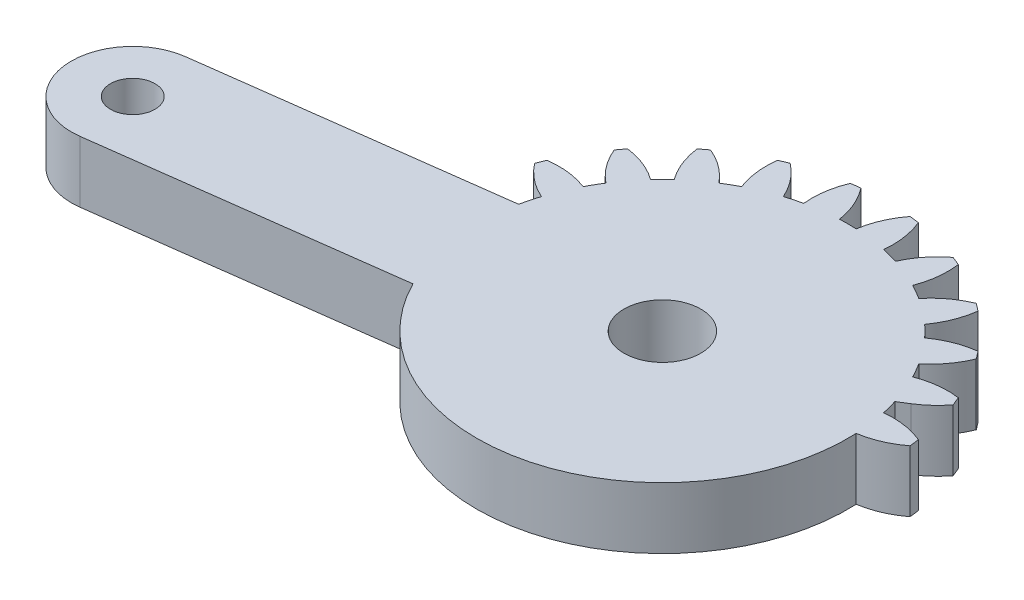
SolidWorks part; units mm, degrees
ref_plane "Front Plane" through (0, 0, 0) normal (0, 0, 1) x (1, 0, 0)
ref_plane "Top Plane" through (0, 0, 0) normal (0, 1, 0) x (1, 0, 0)
ref_plane "Right Plane" through (0, 0, 0) normal (1, 0, 0) x (0, 0, -1)
sketch "Sketch1" plane through (0, 0, 0) normal (0, 1, 0) x (1, 0, 0)
  line L0 (20.6437, 4) -> (2.0816, 4)
  line L1 (2.0816, -4) -> (20.6437, -4)
  arc A0 (2.0816, 4) -> (3.5217, 5.3071) centre (-0.7683, 8.5867) ccw
  arc A1 (3.5217, 5.3071) -> (3.2829, 5.8838) centre (-10.1063, 0) ccw
  arc A2 (3.2829, 5.8838) -> (0.6271, 5.5703) centre (2.5684, 0.5313) ccw
  arc A3 (0.6271, 5.5703) -> (0.0844, 6.5103) centre (-10.1063, 0) ccw
  arc A4 (0.0844, 6.5103) -> (1.6838, 8.6535) centre (-3.3089, 10.711) ccw
  arc A5 (1.6838, 8.6535) -> (1.3038, 9.1487) centre (-10.1063, 0) ccw
  arc A6 (1.3038, 9.1487) -> (-1.1803, 8.1585) centre (1.999, 3.7936) ccw
  arc A7 (-1.1803, 8.1585) -> (-1.9479, 8.926) centre (-10.1063, 0) ccw
  arc A8 (-1.9479, 8.926) -> (-0.9576, 11.4102) centre (-6.3127, 12.1053) ccw
  arc A9 (-0.9576, 11.4102) -> (-1.4528, 11.7901) centre (-10.1063, 0) ccw
  arc A10 (-1.4528, 11.7901) -> (-3.596, 10.1907) centre (0.6046, 6.7975) ccw
  arc A11 (-3.596, 10.1907) -> (-4.5361, 10.7334) centre (-10.1063, 0) ccw
  arc A12 (-4.5361, 10.7334) -> (-4.2225, 13.3892) centre (-9.5751, 12.6747) ccw
  arc A13 (-4.2225, 13.3892) -> (-4.7992, 13.6281) centre (-10.1063, 0) ccw
  arc A14 (-4.7992, 13.6281) -> (-6.4554, 11.5285) centre (-1.5196, 9.3381) ccw
  arc A15 (-6.4554, 11.5285) -> (-7.5039, 11.8094) centre (-10.1063, 0) ccw
  arc A16 (-7.5039, 11.8094) -> (-7.8884, 14.4558) centre (-12.8736, 12.3803) ccw
  arc A17 (-7.8884, 14.4558) -> (-8.5072, 14.5373) centre (-10.1063, 0) ccw
  arc A18 (-8.5072, 14.5373) -> (-9.5636, 12.0806) centre (-4.2291, 11.2423) ccw
  arc A19 (-9.5636, 12.0806) -> (-10.6491, 12.0806) centre (-10.1063, 0) ccw
  arc A20 (-10.6491, 12.0806) -> (-11.7054, 14.5373) centre (-15.9836, 11.2423) ccw
  arc A21 (-11.7054, 14.5373) -> (-12.3243, 14.4558) centre (-10.1063, 0) ccw
  arc A22 (-12.3243, 14.4558) -> (-12.7088, 11.8094) centre (-7.3391, 12.3803) ccw
  arc A23 (-12.7088, 11.8094) -> (-13.7573, 11.5285) centre (-10.1063, 0) ccw
  arc A24 (-13.7573, 11.5285) -> (-15.4135, 13.6281) centre (-18.6931, 9.3381) ccw
  arc A25 (-15.4135, 13.6281) -> (-15.9901, 13.3892) centre (-10.1063, 0) ccw
  arc A26 (-15.9901, 13.3892) -> (-15.6766, 10.7334) centre (-10.6376, 12.6747) ccw
  arc A27 (-15.6766, 10.7334) -> (-16.6166, 10.1907) centre (-10.1063, 0) ccw
  arc A28 (-16.6166, 10.1907) -> (-18.7599, 11.7901) centre (-20.8173, 6.7975) ccw
  arc A29 (-18.7599, 11.7901) -> (-19.255, 11.4102) centre (-10.1063, 0) ccw
  arc A30 (-19.255, 11.4102) -> (-18.2648, 8.926) centre (-13.9, 12.1053) ccw
  arc A31 (-18.2648, 8.926) -> (-19.0324, 8.1585) centre (-10.1063, 0) ccw
  arc A32 (-19.0324, 8.1585) -> (-21.5165, 9.1487) centre (-22.2117, 3.7936) ccw
  arc A33 (-21.5165, 9.1487) -> (-21.8965, 8.6535) centre (-10.1063, 0) ccw
  arc A34 (-21.8965, 8.6535) -> (-20.2971, 6.5103) centre (-16.9038, 10.711) ccw
  arc A35 (-20.2971, 6.5103) -> (-20.8398, 5.5703) centre (-10.1063, 0) ccw
  arc A36 (-20.8398, 5.5703) -> (-23.4956, 5.8838) centre (-22.7811, 0.5313) ccw
  arc A37 (-23.4956, 5.8838) -> (-23.7344, 5.3071) centre (-10.1063, 0) ccw
  arc A38 (-23.7344, 5.3071) -> (-21.6348, 3.6509) centre (-19.4444, 8.5867) ccw
  arc A39 (-21.6348, 3.6509) -> (-21.9157, 2.6025) centre (-10.1063, 0) ccw
  arc A40 (-21.9157, 2.6025) -> (-24.5622, 2.2179) centre (-22.4867, -2.7673) ccw
  arc A41 (-24.5622, 2.2179) -> (-24.6437, 1.5991) centre (-10.1063, 0) ccw
  arc A42 (-24.6437, 1.5991) -> (-22.1869, 0.5427) centre (-21.3486, 5.8773) ccw
  arc A43 (-22.1869, 0.5427) -> (-22.1869, -0.5427) centre (-10.1063, 0) ccw
  arc A44 (-22.1869, -0.5427) -> (-24.6437, -1.5991) centre (-21.3486, -5.8773) ccw
  arc A45 (-24.6437, -1.5991) -> (-24.5622, -2.2179) centre (-10.1063, 0) ccw
  arc A46 (-24.5622, -2.2179) -> (-21.9157, -2.6025) centre (-22.4867, 2.7673) ccw
  arc A47 (-21.9157, -2.6025) -> (-21.6348, -3.6509) centre (-10.1063, 0) ccw
  arc A48 (-21.6348, -3.6509) -> (-23.7344, -5.3071) centre (-19.4444, -8.5867) ccw
  arc A49 (-23.7344, -5.3071) -> (-23.4956, -5.8838) centre (-10.1063, 0) ccw
  arc A50 (-23.4956, -5.8838) -> (-20.8398, -5.5703) centre (-22.7811, -0.5313) ccw
  arc A51 (-20.8398, -5.5703) -> (-20.2971, -6.5103) centre (-10.1063, 0) ccw
  arc A52 (-20.2971, -6.5103) -> (-21.8965, -8.6535) centre (-16.9038, -10.711) ccw
  arc A53 (-21.8965, -8.6535) -> (-21.5165, -9.1487) centre (-10.1063, 0) ccw
  arc A54 (-21.5165, -9.1487) -> (-19.0324, -8.1585) centre (-22.2117, -3.7936) ccw
  arc A55 (-19.0324, -8.1585) -> (-18.2648, -8.926) centre (-10.1063, 0) ccw
  arc A56 (-18.2648, -8.926) -> (-19.255, -11.4102) centre (-13.9, -12.1053) ccw
  arc A57 (-19.255, -11.4102) -> (-18.7599, -11.7901) centre (-10.1063, 0) ccw
  arc A58 (-18.7599, -11.7901) -> (-16.6166, -10.1907) centre (-20.8173, -6.7975) ccw
  arc A59 (-16.6166, -10.1907) -> (-15.6766, -10.7334) centre (-10.1063, 0) ccw
  arc A60 (-15.6766, -10.7334) -> (-15.9901, -13.3892) centre (-10.6376, -12.6747) ccw
  arc A61 (-15.9901, -13.3892) -> (-15.4135, -13.6281) centre (-10.1063, 0) ccw
  arc A62 (-15.4135, -13.6281) -> (-13.7573, -11.5285) centre (-18.6931, -9.3381) ccw
  arc A63 (-13.7573, -11.5285) -> (-12.7088, -11.8094) centre (-10.1063, 0) ccw
  arc A64 (-12.7088, -11.8094) -> (-12.3243, -14.4558) centre (-7.3391, -12.3803) ccw
  arc A65 (-12.3243, -14.4558) -> (-11.7054, -14.5373) centre (-10.1063, 0) ccw
  arc A66 (-11.7054, -14.5373) -> (-10.6491, -12.0806) centre (-15.9836, -11.2423) ccw
  arc A67 (-10.6491, -12.0806) -> (-9.5636, -12.0806) centre (-10.1063, 0) ccw
  arc A68 (-9.5636, -12.0806) -> (-8.5072, -14.5373) centre (-4.2291, -11.2423) ccw
  arc A69 (-8.5072, -14.5373) -> (-7.8884, -14.4558) centre (-10.1063, 0) ccw
  arc A70 (-7.8884, -14.4558) -> (-7.5039, -11.8094) centre (-12.8736, -12.3803) ccw
  arc A71 (-7.5039, -11.8094) -> (-6.4554, -11.5285) centre (-10.1063, 0) ccw
  arc A72 (-6.4554, -11.5285) -> (-4.7992, -13.6281) centre (-1.5196, -9.3381) ccw
  arc A73 (-4.7992, -13.6281) -> (-4.2225, -13.3892) centre (-10.1063, 0) ccw
  arc A74 (-4.2225, -13.3892) -> (-4.5361, -10.7334) centre (-9.5751, -12.6747) ccw
  arc A75 (-4.5361, -10.7334) -> (-3.596, -10.1907) centre (-10.1063, 0) ccw
  arc A76 (-3.596, -10.1907) -> (-1.4528, -11.7901) centre (0.6046, -6.7975) ccw
  arc A77 (-1.4528, -11.7901) -> (-0.9576, -11.4102) centre (-10.1063, 0) ccw
  arc A78 (-0.9576, -11.4102) -> (-1.9479, -8.926) centre (-6.3127, -12.1053) ccw
  arc A79 (-1.9479, -8.926) -> (-1.1803, -8.1585) centre (-10.1063, 0) ccw
  arc A80 (-1.1803, -8.1585) -> (1.3038, -9.1487) centre (1.999, -3.7936) ccw
  arc A81 (1.3038, -9.1487) -> (1.6838, -8.6535) centre (-10.1063, 0) ccw
  arc A82 (1.6838, -8.6535) -> (0.0844, -6.5103) centre (-3.3089, -10.711) ccw
  arc A83 (0.0844, -6.5103) -> (0.6271, -5.5703) centre (-10.1063, 0) ccw
  arc A84 (0.6271, -5.5703) -> (3.2829, -5.8838) centre (2.5684, -0.5313) ccw
  arc A85 (3.2829, -5.8838) -> (3.5217, -5.3071) centre (-10.1063, 0) ccw
  arc A86 (3.5217, -5.3071) -> (2.0816, -4) centre (-0.7683, -8.5867) ccw
  arc A87 (20.6437, -4) -> (20.6437, 4) centre (20.6437, 0) ccw
  circle A88 centre (-10.1063, 0) radius 1.5
  circle A89 centre (20.6437, 0) radius 1.5
  dimension "D1" = 3
  dimension "D2" = 3
extrude "Boss-Extrude1" add sketch "Sketch1" along normal blind 4
sketch "Sketch3" plane through (0, 4, 0) normal (0, 1, 0) x (1, 0, 0)
  line L0 (-10.1063, 0) -> (-40.8563, 0) construction
  line L1 (-10.1063, 0) -> (-40.5933, -4.0137)
  line L2 (-10.6284, 3.9658) -> (-41.1154, -0.0479)
  line L3 (-9.5842, -3.9658) -> (-40.0712, -7.9795)
  line L4 (-10.1063, 0) -> (-4.5096, 13.5117) construction
  line L5 (-10.1063, 0) -> (-8.1974, 14.4999) construction
  circle A0 centre (-10.1063, 0) radius 1.5
  circle A1 centre (20.6437, 0) radius 1.5 construction
  circle A2 centre (20.6437, 0) radius 1.5
  circle A3 centre (-40.5933, -4.0137) radius 1.45
  circle A4 centre (-40.5933, -4.0137) radius 4
  circle A5 centre (-10.1063, 0) radius 4
  arc A6 (-4.2225, 13.3892) -> (-4.7992, 13.6281) centre (-10.1063, 0) ccw construction
  arc A7 (-7.8884, 14.4558) -> (-8.5072, 14.5373) centre (-10.1063, 0) ccw construction
  dimension "D2" = 3
  dimension "D5" = 2.9
  dimension "D6" = 8
  dimension "D7" = 8
  dimension "D1" = 30.75
  dimension "D4" = 7.5
extrude "Boss-Extrude2" add sketch "Sketch3" against normal blind 4
sketch "Sketch4" plane through (0, 4, 0) normal (0, 1, 0) x (1, 0, 0)
  line L0 (20.6437, 4) -> (2.0816, 4) construction
  line L1 (2.0816, -4) -> (20.6437, -4) construction
  line L2 (20.6437, 4) -> (2.0816, 4)
  line L3 (2.0816, -4) -> (20.6437, -4)
  line L4 (2.0816, 4) -> (1.4381, 3.6001)
  line L5 (-21.6245, -5.5509) -> (-20.8986, -5.4553)
  line L6 (-10.1063, 0) -> (0.0844, 6.5103) construction
  line L7 (-10.1063, 0) -> (1.9742, 0.5427) construction
  line L8 (-24.5755, 2.1296) -> (-41.1154, -0.0479)
  line L9 (-40.0712, -7.9795) -> (-23.5312, -5.8019)
  line L10 (2.0816, -4) -> (20.6437, -4)
  line L11 (20.6437, 4) -> (2.0816, 4)
  line L12 (-21.9429, 2.4762) -> (-41.1154, -0.0479)
  line L13 (-40.0712, -7.9795) -> (-21.6245, -5.5509)
  line L14 (2.0816, -4) -> (20.6437, -4)
  line L15 (20.6437, 4) -> (2.0816, 4)
  circle A0 centre (-10.1063, 0) radius 12.0927
  arc A1 (3.2829, 5.8838) -> (0.6271, 5.5703) centre (2.5684, 0.5313) ccw construction
  arc A2 (3.5217, 5.3071) -> (3.2829, 5.8838) centre (-10.1063, 0) ccw construction
  arc A3 (2.0816, 4) -> (3.5217, 5.3071) centre (-0.7683, 8.5867) ccw construction
  arc A4 (20.6437, -4) -> (20.6437, 4) centre (20.6437, 0) ccw construction
  arc A5 (3.5217, -5.3071) -> (2.0816, -4) centre (-0.7683, -8.5867) ccw construction
  arc A6 (3.2829, -5.8838) -> (3.5217, -5.3071) centre (-10.1063, 0) ccw construction
  arc A7 (0.6271, -5.5703) -> (3.2829, -5.8838) centre (2.5684, -0.5313) ccw construction
  arc A8 (3.2829, 5.8838) -> (0.6271, 5.5703) centre (2.5684, 0.5313) ccw
  arc A9 (3.5217, 5.3071) -> (3.2829, 5.8838) centre (-10.1063, 0) ccw
  arc A10 (2.0816, 4) -> (3.5217, 5.3071) centre (-0.7683, 8.5867) ccw
  arc A11 (20.6437, -4) -> (20.6437, 4) centre (20.6437, 0) ccw
  arc A12 (3.5217, -5.3071) -> (2.0816, -4) centre (-0.7683, -8.5867) ccw
  arc A13 (3.2829, -5.8838) -> (3.5217, -5.3071) centre (-10.1063, 0) ccw
  arc A14 (0.6271, -5.5703) -> (3.2829, -5.8838) centre (2.5684, -0.5313) ccw
  arc A15 (1.9742, 0.5427) -> (4.431, 1.5991) centre (1.1359, 5.8773) ccw
  arc A16 (4.3495, 2.2179) -> (1.7031, 2.6025) centre (2.274, -2.7673) ccw
  arc A17 (4.431, 1.5991) -> (4.3495, 2.2179) centre (-10.1063, 0) ccw
  arc A95 (-21.6348, 3.6509) -> (-21.9157, 2.6025) centre (-10.1063, 0) ccw
  arc A96 (-41.1154, -0.0479) -> (-40.0712, -7.9795) centre (-40.5933, -4.0137) ccw
  arc A97 (-20.2971, -6.5103) -> (-21.8965, -8.6535) centre (-16.9038, -10.711) ccw
  arc A98 (-21.8965, -8.6535) -> (-21.5165, -9.1487) centre (-10.1063, 0) ccw
  arc A99 (-21.5165, -9.1487) -> (-19.0324, -8.1585) centre (-22.2117, -3.7936) ccw
  arc A100 (-19.0324, -8.1585) -> (-18.2648, -8.926) centre (-10.1063, 0) ccw
  arc A101 (-18.2648, -8.926) -> (-19.255, -11.4102) centre (-13.9, -12.1053) ccw
  arc A102 (-19.255, -11.4102) -> (-18.7599, -11.7901) centre (-10.1063, 0) ccw
  arc A103 (-18.7599, -11.7901) -> (-16.6166, -10.1907) centre (-20.8173, -6.7975) ccw
  arc A104 (-16.6166, -10.1907) -> (-15.6766, -10.7334) centre (-10.1063, 0) ccw
  arc A105 (-15.6766, -10.7334) -> (-15.9901, -13.3892) centre (-10.6376, -12.6747) ccw
  arc A106 (-15.9901, -13.3892) -> (-15.4135, -13.6281) centre (-10.1063, 0) ccw
  arc A107 (-15.4135, -13.6281) -> (-13.7573, -11.5285) centre (-18.6931, -9.3381) ccw
  arc A108 (-13.7573, -11.5285) -> (-12.7088, -11.8094) centre (-10.1063, 0) ccw
  arc A109 (-12.7088, -11.8094) -> (-12.3243, -14.4558) centre (-7.3391, -12.3803) ccw
  arc A110 (-12.3243, -14.4558) -> (-11.7054, -14.5373) centre (-10.1063, 0) ccw
  arc A111 (-11.7054, -14.5373) -> (-10.6491, -12.0806) centre (-15.9836, -11.2423) ccw
  arc A112 (-10.6491, -12.0806) -> (-9.5636, -12.0806) centre (-10.1063, 0) ccw
  arc A113 (-9.5636, -12.0806) -> (-8.5072, -14.5373) centre (-4.2291, -11.2423) ccw
  arc A114 (-8.5072, -14.5373) -> (-7.8884, -14.4558) centre (-10.1063, 0) ccw
  arc A115 (-7.8884, -14.4558) -> (-7.5039, -11.8094) centre (-12.8736, -12.3803) ccw
  arc A116 (-7.5039, -11.8094) -> (-6.4554, -11.5285) centre (-10.1063, 0) ccw
  arc A117 (-6.4554, -11.5285) -> (-4.7992, -13.6281) centre (-1.5196, -9.3381) ccw
  arc A118 (-4.7992, -13.6281) -> (-4.2225, -13.3892) centre (-10.1063, 0) ccw
  arc A119 (-4.2225, -13.3892) -> (-4.5361, -10.7334) centre (-9.5751, -12.6747) ccw
  arc A120 (-4.5361, -10.7334) -> (-3.596, -10.1907) centre (-10.1063, 0) ccw
  arc A121 (-3.596, -10.1907) -> (-1.4528, -11.7901) centre (0.6046, -6.7975) ccw
  arc A122 (-1.4528, -11.7901) -> (-0.9576, -11.4102) centre (-10.1063, 0) ccw
  arc A123 (-0.9576, -11.4102) -> (-1.9479, -8.926) centre (-6.3127, -12.1053) ccw
  arc A124 (-1.9479, -8.926) -> (-1.1803, -8.1585) centre (-10.1063, 0) ccw
  arc A125 (-1.1803, -8.1585) -> (1.3038, -9.1487) centre (1.999, -3.7936) ccw
  arc A126 (1.3038, -9.1487) -> (1.6838, -8.6535) centre (-10.1063, 0) ccw
  arc A127 (1.6838, -8.6535) -> (0.0844, -6.5103) centre (-3.3089, -10.711) ccw
  arc A128 (0.0844, -6.5103) -> (0.6271, -5.5703) centre (-10.1063, 0) ccw
  arc A129 (0.6271, -5.5703) -> (3.2829, -5.8838) centre (2.5684, -0.5313) ccw
  arc A130 (3.2829, -5.8838) -> (3.5217, -5.3071) centre (-10.1063, 0) ccw
  arc A131 (3.5217, -5.3071) -> (2.0816, -4) centre (-0.7683, -8.5867) ccw
  arc A132 (20.6437, -4) -> (20.6437, 4) centre (20.6437, 0) ccw
  arc A133 (2.0816, 4) -> (3.5217, 5.3071) centre (-0.7683, 8.5867) ccw
  arc A134 (3.5217, 5.3071) -> (3.2829, 5.8838) centre (-10.1063, 0) ccw
  arc A135 (3.2829, 5.8838) -> (0.6271, 5.5703) centre (2.5684, 0.5313) ccw
  arc A136 (0.6271, 5.5703) -> (0.0844, 6.5103) centre (-10.1063, 0) ccw
  arc A137 (0.0844, 6.5103) -> (1.6838, 8.6535) centre (-3.3089, 10.711) ccw
  arc A138 (1.6838, 8.6535) -> (1.3038, 9.1487) centre (-10.1063, 0) ccw
  arc A139 (1.3038, 9.1487) -> (-1.1803, 8.1585) centre (1.999, 3.7936) ccw
  arc A140 (-1.1803, 8.1585) -> (-1.9479, 8.926) centre (-10.1063, 0) ccw
  arc A141 (-1.9479, 8.926) -> (-0.9576, 11.4102) centre (-6.3127, 12.1053) ccw
  arc A142 (-0.9576, 11.4102) -> (-1.4528, 11.7901) centre (-10.1063, 0) ccw
  arc A143 (-1.4528, 11.7901) -> (-3.596, 10.1907) centre (0.6046, 6.7975) ccw
  arc A144 (-3.596, 10.1907) -> (-4.5361, 10.7334) centre (-10.1063, 0) ccw
  arc A145 (-4.5361, 10.7334) -> (-4.2225, 13.3892) centre (-9.5751, 12.6747) ccw
  arc A146 (-4.2225, 13.3892) -> (-4.7992, 13.6281) centre (-10.1063, 0) ccw
  arc A147 (-4.7992, 13.6281) -> (-6.4554, 11.5285) centre (-1.5196, 9.3381) ccw
  arc A148 (-6.4554, 11.5285) -> (-7.5039, 11.8094) centre (-10.1063, 0) ccw
  arc A149 (-7.5039, 11.8094) -> (-7.8884, 14.4558) centre (-12.8736, 12.3803) ccw
  arc A150 (-7.8884, 14.4558) -> (-8.5072, 14.5373) centre (-10.1063, 0) ccw
  arc A151 (-8.5072, 14.5373) -> (-9.5636, 12.0806) centre (-4.2291, 11.2423) ccw
  arc A152 (-9.5636, 12.0806) -> (-10.6491, 12.0806) centre (-10.1063, 0) ccw
  arc A153 (-10.6491, 12.0806) -> (-11.7054, 14.5373) centre (-15.9836, 11.2423) ccw
  arc A154 (-11.7054, 14.5373) -> (-12.3243, 14.4558) centre (-10.1063, 0) ccw
  arc A155 (-12.3243, 14.4558) -> (-12.7088, 11.8094) centre (-7.3391, 12.3803) ccw
  arc A156 (-12.7088, 11.8094) -> (-13.7573, 11.5285) centre (-10.1063, 0) ccw
  arc A157 (-13.7573, 11.5285) -> (-15.4135, 13.6281) centre (-18.6931, 9.3381) ccw
  arc A158 (-15.4135, 13.6281) -> (-15.9901, 13.3892) centre (-10.1063, 0) ccw
  arc A159 (-15.9901, 13.3892) -> (-15.6766, 10.7334) centre (-10.6376, 12.6747) ccw
  arc A160 (-15.6766, 10.7334) -> (-16.6166, 10.1907) centre (-10.1063, 0) ccw
  arc A161 (-16.6166, 10.1907) -> (-18.7599, 11.7901) centre (-20.8173, 6.7975) ccw
  arc A162 (-18.7599, 11.7901) -> (-19.255, 11.4102) centre (-10.1063, 0) ccw
  arc A163 (-19.255, 11.4102) -> (-18.2648, 8.926) centre (-13.9, 12.1053) ccw
  arc A164 (-18.2648, 8.926) -> (-19.0324, 8.1585) centre (-10.1063, 0) ccw
  arc A165 (-19.0324, 8.1585) -> (-21.5165, 9.1487) centre (-22.2117, 3.7936) ccw
  arc A166 (-21.5165, 9.1487) -> (-21.8965, 8.6535) centre (-10.1063, 0) ccw
  arc A167 (-21.8965, 8.6535) -> (-20.2971, 6.5103) centre (-16.9038, 10.711) ccw
  arc A168 (-20.2971, 6.5103) -> (-20.8398, 5.5703) centre (-10.1063, 0) ccw
  arc A169 (-20.8398, 5.5703) -> (-23.4956, 5.8838) centre (-22.7811, 0.5313) ccw
  arc A170 (-23.4956, 5.8838) -> (-23.7344, 5.3071) centre (-10.1063, 0) ccw
  arc A171 (-23.7344, 5.3071) -> (-21.6348, 3.6509) centre (-19.4444, 8.5867) ccw
  arc A172 (-21.6348, 3.6509) -> (-21.9157, 2.6025) centre (-10.1063, 0) ccw
  arc A175 (-23.4956, -5.8838) -> (-20.8398, -5.5703) centre (-22.7811, -0.5313) ccw
  arc A176 (-41.1154, -0.0479) -> (-40.0712, -7.9795) centre (-40.5933, -4.0137) ccw
  arc A177 (-20.2971, -6.5103) -> (-21.8965, -8.6535) centre (-16.9038, -10.711) ccw
  arc A178 (-21.8965, -8.6535) -> (-21.5165, -9.1487) centre (-10.1063, 0) ccw
  arc A179 (-21.5165, -9.1487) -> (-19.0324, -8.1585) centre (-22.2117, -3.7936) ccw
  arc A180 (-19.0324, -8.1585) -> (-18.2648, -8.926) centre (-10.1063, 0) ccw
  arc A181 (-18.2648, -8.926) -> (-19.255, -11.4102) centre (-13.9, -12.1053) ccw
  arc A182 (-19.255, -11.4102) -> (-18.7599, -11.7901) centre (-10.1063, 0) ccw
  arc A183 (-18.7599, -11.7901) -> (-16.6166, -10.1907) centre (-20.8173, -6.7975) ccw
  arc A184 (-16.6166, -10.1907) -> (-15.6766, -10.7334) centre (-10.1063, 0) ccw
  arc A185 (-15.6766, -10.7334) -> (-15.9901, -13.3892) centre (-10.6376, -12.6747) ccw
  arc A186 (-15.9901, -13.3892) -> (-15.4135, -13.6281) centre (-10.1063, 0) ccw
  arc A187 (-15.4135, -13.6281) -> (-13.7573, -11.5285) centre (-18.6931, -9.3381) ccw
  arc A188 (-13.7573, -11.5285) -> (-12.7088, -11.8094) centre (-10.1063, 0) ccw
  arc A189 (-12.7088, -11.8094) -> (-12.3243, -14.4558) centre (-7.3391, -12.3803) ccw
  arc A190 (-12.3243, -14.4558) -> (-11.7054, -14.5373) centre (-10.1063, 0) ccw
  arc A191 (-11.7054, -14.5373) -> (-10.6491, -12.0806) centre (-15.9836, -11.2423) ccw
  arc A192 (-10.6491, -12.0806) -> (-9.5636, -12.0806) centre (-10.1063, 0) ccw
  arc A193 (-9.5636, -12.0806) -> (-8.5072, -14.5373) centre (-4.2291, -11.2423) ccw
  arc A194 (-8.5072, -14.5373) -> (-7.8884, -14.4558) centre (-10.1063, 0) ccw
  arc A195 (-7.8884, -14.4558) -> (-7.5039, -11.8094) centre (-12.8736, -12.3803) ccw
  arc A196 (-7.5039, -11.8094) -> (-6.4554, -11.5285) centre (-10.1063, 0) ccw
  arc A197 (-6.4554, -11.5285) -> (-4.7992, -13.6281) centre (-1.5196, -9.3381) ccw
  arc A198 (-4.7992, -13.6281) -> (-4.2225, -13.3892) centre (-10.1063, 0) ccw
  arc A199 (-4.2225, -13.3892) -> (-4.5361, -10.7334) centre (-9.5751, -12.6747) ccw
  arc A200 (-4.5361, -10.7334) -> (-3.596, -10.1907) centre (-10.1063, 0) ccw
  arc A201 (-3.596, -10.1907) -> (-1.4528, -11.7901) centre (0.6046, -6.7975) ccw
  arc A202 (-1.4528, -11.7901) -> (-0.9576, -11.4102) centre (-10.1063, 0) ccw
  arc A203 (-0.9576, -11.4102) -> (-1.9479, -8.926) centre (-6.3127, -12.1053) ccw
  arc A204 (-1.9479, -8.926) -> (-1.1803, -8.1585) centre (-10.1063, 0) ccw
  arc A205 (-1.1803, -8.1585) -> (1.3038, -9.1487) centre (1.999, -3.7936) ccw
  arc A206 (1.3038, -9.1487) -> (1.6838, -8.6535) centre (-10.1063, 0) ccw
  arc A207 (1.6838, -8.6535) -> (0.0844, -6.5103) centre (-3.3089, -10.711) ccw
  arc A208 (0.0844, -6.5103) -> (0.6271, -5.5703) centre (-10.1063, 0) ccw
  arc A209 (0.6271, -5.5703) -> (3.2829, -5.8838) centre (2.5684, -0.5313) ccw
  arc A210 (3.2829, -5.8838) -> (3.5217, -5.3071) centre (-10.1063, 0) ccw
  arc A211 (3.5217, -5.3071) -> (2.0816, -4) centre (-0.7683, -8.5867) ccw
  arc A212 (20.6437, -4) -> (20.6437, 4) centre (20.6437, 0) ccw
  arc A213 (2.0816, 4) -> (3.5217, 5.3071) centre (-0.7683, 8.5867) ccw
  arc A214 (3.5217, 5.3071) -> (3.2829, 5.8838) centre (-10.1063, 0) ccw
  arc A215 (3.2829, 5.8838) -> (0.6271, 5.5703) centre (2.5684, 0.5313) ccw
  arc A216 (0.6271, 5.5703) -> (0.0844, 6.5103) centre (-10.1063, 0) ccw
  arc A217 (0.0844, 6.5103) -> (1.6838, 8.6535) centre (-3.3089, 10.711) ccw
  arc A218 (1.6838, 8.6535) -> (1.3038, 9.1487) centre (-10.1063, 0) ccw
  arc A219 (1.3038, 9.1487) -> (-1.1803, 8.1585) centre (1.999, 3.7936) ccw
  arc A220 (-1.1803, 8.1585) -> (-1.9479, 8.926) centre (-10.1063, 0) ccw
  arc A221 (-1.9479, 8.926) -> (-0.9576, 11.4102) centre (-6.3127, 12.1053) ccw
  arc A222 (-0.9576, 11.4102) -> (-1.4528, 11.7901) centre (-10.1063, 0) ccw
  arc A223 (-1.4528, 11.7901) -> (-3.596, 10.1907) centre (0.6046, 6.7975) ccw
  arc A224 (-3.596, 10.1907) -> (-4.5361, 10.7334) centre (-10.1063, 0) ccw
  arc A225 (-4.5361, 10.7334) -> (-4.2225, 13.3892) centre (-9.5751, 12.6747) ccw
  arc A226 (-4.2225, 13.3892) -> (-4.7992, 13.6281) centre (-10.1063, 0) ccw
  arc A227 (-4.7992, 13.6281) -> (-6.4554, 11.5285) centre (-1.5196, 9.3381) ccw
  arc A228 (-6.4554, 11.5285) -> (-7.5039, 11.8094) centre (-10.1063, 0) ccw
  arc A229 (-7.5039, 11.8094) -> (-7.8884, 14.4558) centre (-12.8736, 12.3803) ccw
  arc A230 (-7.8884, 14.4558) -> (-8.5072, 14.5373) centre (-10.1063, 0) ccw
  arc A231 (-8.5072, 14.5373) -> (-9.5636, 12.0806) centre (-4.2291, 11.2423) ccw
  arc A232 (-9.5636, 12.0806) -> (-10.6491, 12.0806) centre (-10.1063, 0) ccw
  arc A233 (-10.6491, 12.0806) -> (-11.7054, 14.5373) centre (-15.9836, 11.2423) ccw
  arc A234 (-11.7054, 14.5373) -> (-12.3243, 14.4558) centre (-10.1063, 0) ccw
  arc A235 (-12.3243, 14.4558) -> (-12.7088, 11.8094) centre (-7.3391, 12.3803) ccw
  arc A236 (-12.7088, 11.8094) -> (-13.7573, 11.5285) centre (-10.1063, 0) ccw
  arc A237 (-13.7573, 11.5285) -> (-15.4135, 13.6281) centre (-18.6931, 9.3381) ccw
  arc A238 (-15.4135, 13.6281) -> (-15.9901, 13.3892) centre (-10.1063, 0) ccw
  arc A239 (-15.9901, 13.3892) -> (-15.6766, 10.7334) centre (-10.6376, 12.6747) ccw
  arc A240 (-15.6766, 10.7334) -> (-16.6166, 10.1907) centre (-10.1063, 0) ccw
  arc A241 (-16.6166, 10.1907) -> (-18.7599, 11.7901) centre (-20.8173, 6.7975) ccw
  arc A242 (-18.7599, 11.7901) -> (-19.255, 11.4102) centre (-10.1063, 0) ccw
  arc A243 (-19.255, 11.4102) -> (-18.2648, 8.926) centre (-13.9, 12.1053) ccw
  arc A244 (-18.2648, 8.926) -> (-19.0324, 8.1585) centre (-10.1063, 0) ccw
  arc A245 (-19.0324, 8.1585) -> (-21.5165, 9.1487) centre (-22.2117, 3.7936) ccw
  arc A246 (-21.5165, 9.1487) -> (-21.8965, 8.6535) centre (-10.1063, 0) ccw
  arc A247 (-21.8965, 8.6535) -> (-20.2971, 6.5103) centre (-16.9038, 10.711) ccw
  arc A248 (-20.2971, 6.5103) -> (-20.8398, 5.5703) centre (-10.1063, 0) ccw
  arc A249 (-20.8398, 5.5703) -> (-23.4956, 5.8838) centre (-22.7811, 0.5313) ccw
  arc A250 (-23.4956, 5.8838) -> (-23.7344, 5.3071) centre (-10.1063, 0) ccw
  arc A251 (-23.7344, 5.3071) -> (-21.6348, 3.6509) centre (-19.4444, 8.5867) ccw
  arc A252 (-23.4956, -5.8838) -> (-20.8398, -5.5703) centre (-22.7811, -0.5313) ccw
  arc A253 (-20.8398, -5.5703) -> (-20.2971, -6.5103) centre (-10.1063, 0) ccw
  arc A254 (-20.8398, -5.5703) -> (-20.2971, -6.5103) centre (-10.1063, 0) ccw
  arc A255 (-23.5312, -5.8019) -> (-23.4956, -5.8838) centre (-10.1063, 0) ccw
  arc A256 (-23.5312, -5.8019) -> (-23.4956, -5.8838) centre (-10.1063, 0) ccw
  arc A257 (-21.9157, 2.6025) -> (-24.5622, 2.2179) centre (-22.4867, -2.7673) ccw
  arc A258 (-21.9157, 2.6025) -> (-24.5622, 2.2179) centre (-22.4867, -2.7673) ccw
  arc A259 (-24.5622, 2.2179) -> (-24.5755, 2.1296) centre (-10.1063, 0) ccw
  arc A260 (-24.5622, 2.2179) -> (-24.5755, 2.1296) centre (-10.1063, 0) ccw
  point P40 (-10.1063, 0)
  dimension "D2" = 24.1855
  dimension "D4" = 30
  dimension "D1" = 0
  dimension "D3" = 2
extrude "Cut-Extrude1" cut sketch "Sketch4" against normal blind 4 contours A178 A179 A0 L5 A177 | A182 A183 A0 A181 | A186 A187 A0 A185 | A190 A191 A0 A189 | A194 A195 A0 A193 | A198 A199 A0 A197 | A202 A203 A0 A201 | A206 A207 A0 A205 | A258 A260 L12 A0 | L13 A256 A252 A0 L5 | A0 A14 A13 A12 L3 A11 L2 L4
sketch "Sketch5" plane through (0, 4, 0) normal (0, 1, 0) x (1, 0, 0)
  circle A0 centre (-10.1063, 0) radius 2.5
  circle A1 centre (-5.6063, 0) radius 1.3
  circle A2 centre (-14.6063, 0) radius 1.3
  circle A3 centre (-10.1063, 0) radius 1.5 construction
  dimension "D1" = 5
  dimension "D2" = 2.6
  dimension "D3" = 2.6
  dimension "D4" = 4.5
  dimension "D5" = 9
extrude "Cut-Extrude2" cut sketch "Sketch5" against normal up to next contours A0
